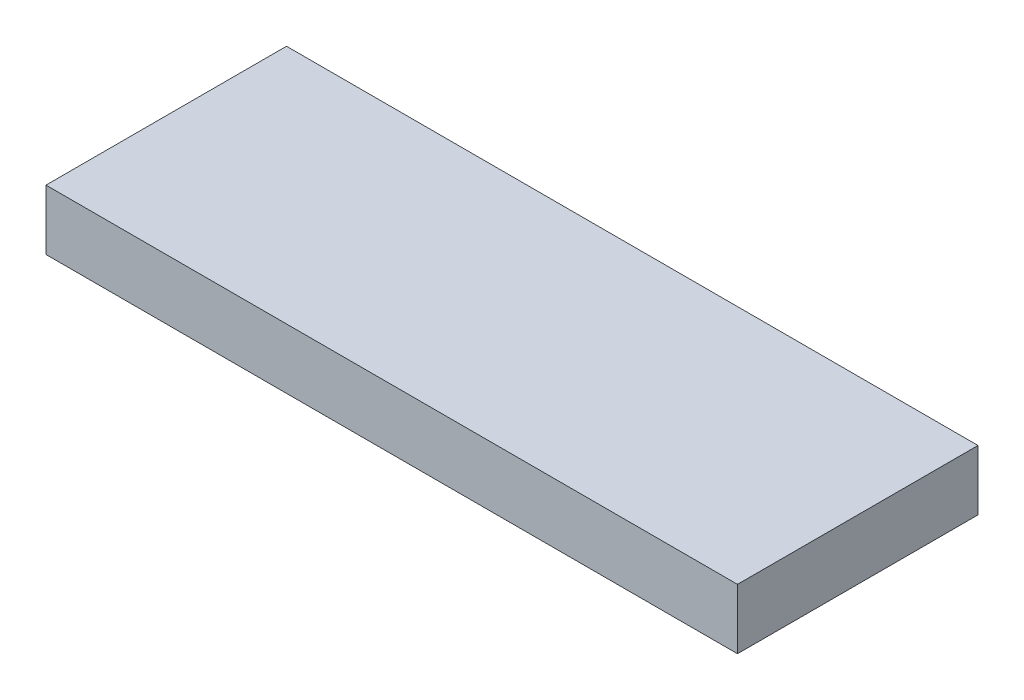
SolidWorks part; units mm, degrees
ref_plane "Front Plane" through (0, 0, 0) normal (0, 0, 1) x (1, 0, 0)
ref_plane "Top Plane" through (0, 0, 0) normal (0, 1, 0) x (1, 0, 0)
ref_plane "Right Plane" through (0, 0, 0) normal (1, 0, 0) x (0, 0, -1)
sketch "Sketch1" plane through (0, 0, 0) normal (0, 1, 0) x (1, 0, 0)
  line L0 (73.025, 25.4) -> (73.025, 0)
  line L1 (0, 0) -> (73.025, 0)
  line L2 (0, 0) -> (0, 25.4)
  line L3 (0, 25.4) -> (73.025, 25.4)
  line L4 (76.2, -13.453) -> (76.2, 25.4) construction
  point P7 (75.003, 38.853)
  point P8 (0, 0)
  dimension "D1" = 25.4
  dimension "D2" = 76.2
  dimension "D3" = 3.175
extrude "Boss-Extrude1" add sketch "Sketch1" along normal blind 6.35
